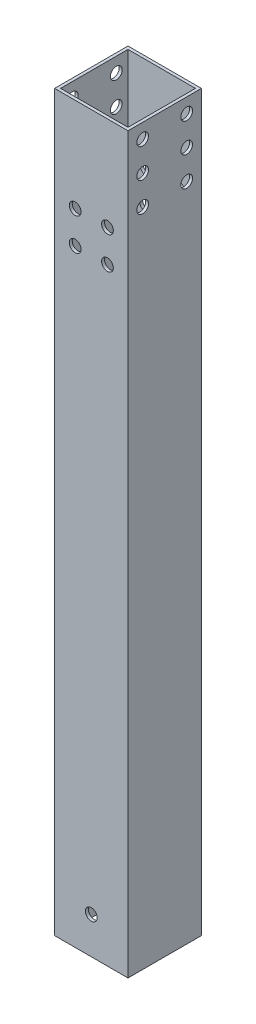
SolidWorks part; units mm, degrees
material "1060 Alloy"
ref_plane "Front Plane" through (0, 0, 0) normal (0, 0, 1) x (1, 0, 0)
ref_plane "Top Plane" through (0, 0, 0) normal (0, 1, 0) x (1, 0, 0)
ref_plane "Right Plane" through (0, 0, 0) normal (1, 0, 0) x (0, 0, -1)
sketch "Sketch1" plane through (0, 0, 0) normal (0, 1, 0) x (1, 0, 0)
  line L0 (-11.5, -11.5) -> (11.5, -11.5)
  line L1 (-12.5, 12.5) -> (12.5, 12.5)
  line L2 (-12.5, 12.5) -> (-12.5, -12.5)
  line L3 (-12.5, -12.5) -> (12.5, -12.5)
  line L4 (12.5, 12.5) -> (12.5, -12.5)
  line L5 (-12.5, 12.5) -> (12.5, -12.5) construction
  line L6 (-12.5, -12.5) -> (12.5, 12.5) construction
  line L7 (11.5, 11.5) -> (11.5, -11.5)
  line L8 (-11.5, 11.5) -> (11.5, 11.5)
  line L9 (-11.5, 11.5) -> (-11.5, -11.5)
  point P0 (0, 0)
  dimension "D1" = 25
  dimension "D2" = 25
  dimension "D3" = 1
extrude "Boss-Extrude1" add sketch "Sketch1" along normal blind 250
sketch "Sketch3" plane through (12.5, 0, 0) normal (1, 0, 0) x (0, 0, -1)
  line L0 (0, 0) -> (0, 288.1425) construction
  line L1 (-12.5, 250) -> (12.5, 250) construction
  circle A0 centre (7.5, 245) radius 2
  circle A1 centre (7.5, 235) radius 2
  circle A3 centre (-7.5, 245) radius 2
  circle A5 centre (-7.5, 235) radius 2
  circle A6 centre (7.5, 225) radius 2
  circle A7 centre (-7.5, 225) radius 2
  dimension "D1" = 7.5
  dimension "D5" = 10
  dimension "D11" = 7.5
  dimension "D2" = 7.5
  dimension "D3" = 7.5
  dimension "D4" = 7.5
  dimension "D6" = 7.5
  dimension "D7" = 5
  dimension "D8" = 5
  dimension "D9" = 10
  dimension "D10" = 10
  dimension "D12" = 10
extrude "Cut-Extrude1" cut sketch "Sketch3" against normal blind 25
sketch "Sketch4" plane through (0, 0, 12.5) normal (0, 0, 1) x (1, 0, 0)
  line L0 (-12.5, 250) -> (12.5, 250) construction
  line L1 (12.5, 250) -> (12.5, 0) construction
  circle A0 centre (5.5, 218) radius 2
  circle A1 centre (5.5, 207) radius 2
  dimension "D1" = 32
  dimension "D2" = 7
  dimension "D3" = 43
  dimension "D4" = 7
extrude "Cut-Extrude2" cut sketch "Sketch4" against normal blind 25
sketch "Sketch5" plane through (0, 0, 12.5) normal (0, 0, 1) x (1, 0, 0)
  line L0 (-12.5, 0) -> (12.5, 0) construction
  line L1 (12.5, 250) -> (12.5, 0) construction
  circle A0 centre (0, 12.5) radius 2
  dimension "D1" = 12.5
  dimension "D2" = 12.5
extrude "Cut-Extrude3" cut sketch "Sketch5" against normal blind 25
mirror "Mirror1" about plane through (0, 0, 0) normal (1, 0, 0) of "Cut-Extrude2"
